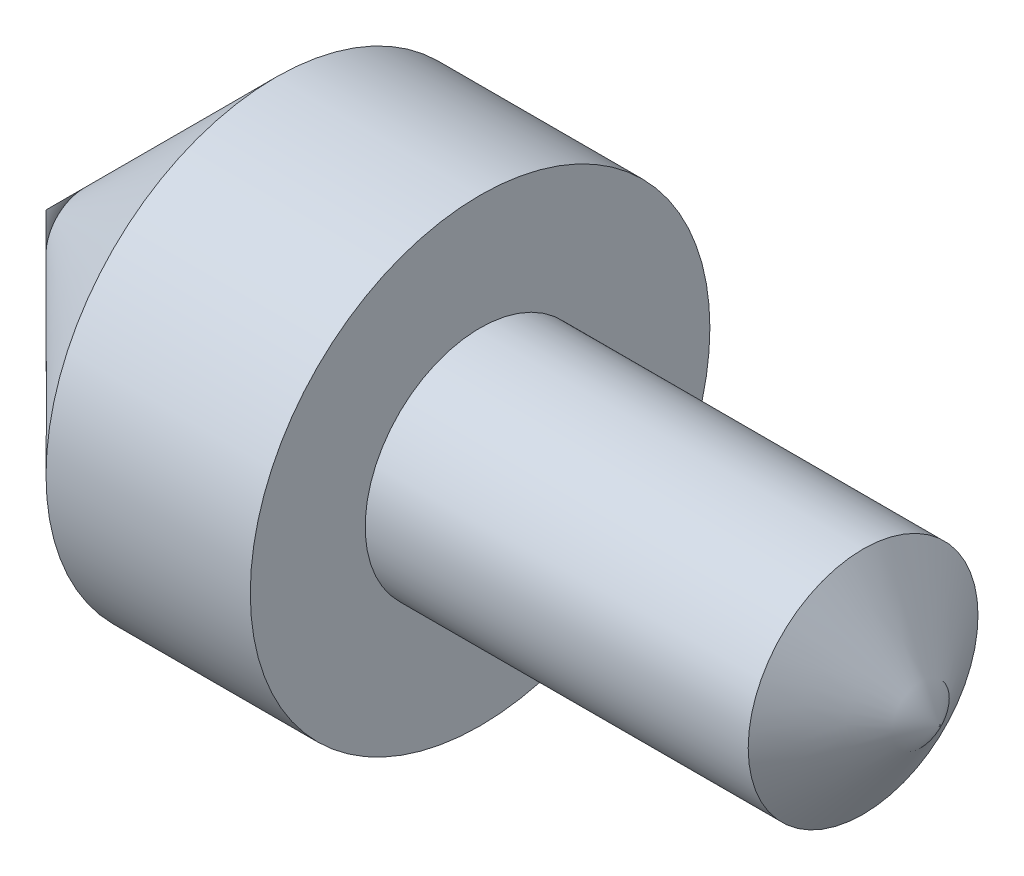
SolidWorks part; units mm, degrees
ref_plane "Plano frontal" through (0, 0, 0) normal (0, 0, 1) x (1, 0, 0)
ref_plane "Plano superior" through (0, 0, 0) normal (0, 1, 0) x (1, 0, 0)
ref_plane "Plano direito" through (0, 0, 0) normal (1, 0, 0) x (0, 0, -1)
sketch "Esboço1" plane through (0, 0, 0) normal (0, 0, 1) x (1, 0, 0)
  line L0 (0, 0) -> (-111.6828, 0) construction
  line L1 (0, 0) -> (-3, -4.5)
  line L2 (-3, -4.5) -> (-18, -4.5)
  line L3 (-18, -4.5) -> (-18, -9)
  line L4 (-18, -9) -> (-26, -9)
  line L5 (-26, -9) -> (-35, 0)
  line L6 (0, 0) -> (-35, 0)
  dimension "D1" = 3
  dimension "D2" = 4.5
  dimension "D3" = 15
  dimension "D4" = 9
  dimension "D5" = 8
  dimension "D6" = 45
  dimension "D7" = 9
revolve "Revolução1" add sketch "Esboço1" angle 360 about L0
